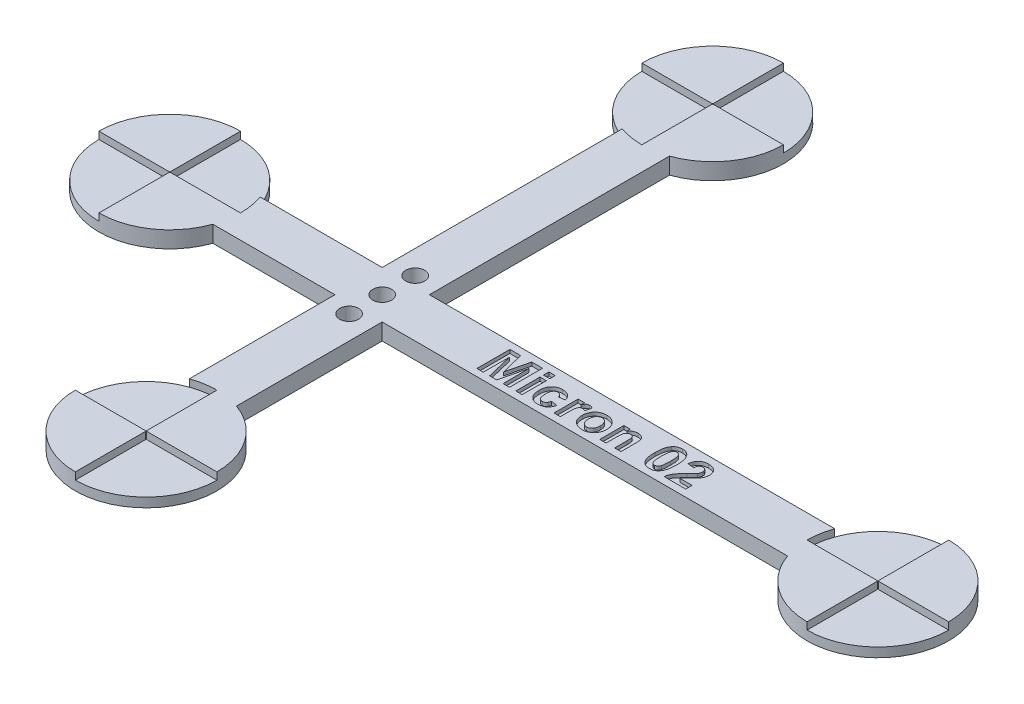
SolidWorks part; units mm, degrees
ref_plane "Front Plane" through (0, 0, 0) normal (0, 0, 1) x (1, 0, 0)
ref_plane "Top Plane" through (0, 0, 0) normal (0, 1, 0) x (1, 0, 0)
ref_plane "Right Plane" through (0, 0, 0) normal (1, 0, 0) x (0, 0, -1)
sketch "Sketch1" plane through (0, 0, 0) normal (0, 1, 0) x (1, 0, 0)
  line L0 (0, 0) -> (150, 0) construction
  line L1 (45, 70) -> (45, -50) construction
  line L2 (40, 55.8579) -> (40, 5)
  line L3 (50, 55.8579) -> (50, 5)
  line L4 (14.1421, 5) -> (40, 5)
  line L5 (14.1421, -5) -> (40, -5)
  line L6 (50, 5) -> (135.8579, 5)
  line L7 (40, -5) -> (40, -35.8579)
  line L8 (50, -5) -> (135.8579, -5)
  line L9 (50, -5) -> (50, -35.8579)
  arc A0 (14.1421, 5) -> (14.1421, -5) centre (0, 0) ccw
  arc A1 (135.8579, -5) -> (135.8579, 5) centre (150, 0) ccw
  arc A2 (50, 55.8579) -> (40, 55.8579) centre (45, 70) ccw
  arc A3 (40, -35.8579) -> (50, -35.8579) centre (45, -50) ccw
  dimension "D1" = 30
  dimension "D3" = 30
  dimension "D5" = 30
  dimension "D6" = 30
  dimension "D2" = 150
  dimension "D4" = 45
  dimension "D7" = 70
  dimension "D8" = 120
  dimension "D9" = 5
  dimension "D10" = 5
  dimension "D11" = 5
  dimension "D12" = 5
extrude "Boss-Extrude1" add sketch "Sketch1" along normal blind 3.5
sketch "Sketch2" plane through (0, 3.5, 0) normal (0, 1, 0) x (1, 0, 0)
  line L0 (45, -65) -> (45, -50.1)
  line L1 (-15, 0) -> (-0.1, 0)
  line L2 (30, 70) -> (44.9, 70)
  line L3 (0, 15) -> (0, 0.1)
  line L4 (150, 15) -> (150, 0.1)
  line L5 (30, -50) -> (44.9, -50)
  line L6 (45.1, 70) -> (60, 70)
  line L7 (45, 70.1) -> (45, 85)
  line L8 (45, 55) -> (45, 69.9)
  line L9 (45, -49.9) -> (45, -35)
  line L10 (45.1, -50) -> (60, -50)
  line L11 (135, 0) -> (149.9, 0)
  line L12 (0.1, 0) -> (15, 0)
  line L13 (0, -0.1) -> (0, -15)
  line L14 (150, -0.1) -> (150, -15)
  line L15 (150.1, 0) -> (165, 0)
  arc A0 (15, 0) -> (0, 15) centre (0, 0) ccw
  arc A1 (150, -15) -> (165, 0) centre (150, 0) ccw
  arc A2 (30, 70) -> (45, 55) centre (45, 70) ccw
  arc A3 (45, -35) -> (30, -50) centre (45, -50) ccw
  arc A4 (0, 0.1) -> (-0.1, 0) centre (0, 0) ccw
  arc A5 (45, 69.9) -> (45.1, 70) centre (45, 70) ccw
  arc A6 (149.9, 0) -> (150, -0.1) centre (150, 0) ccw
  arc A7 (44.9, -50) -> (45, -50.1) centre (45, -50) ccw
  arc A8 (45, 70.1) -> (44.9, 70) centre (45, 70) ccw
  arc A9 (60, 70) -> (45, 85) centre (45, 70) ccw
  arc A10 (45, -65) -> (60, -50) centre (45, -50) ccw
  arc A11 (45.1, -50) -> (45, -49.9) centre (45, -50) ccw
  arc A12 (-15, 0) -> (0, -15) centre (0, 0) ccw
  arc A13 (0, -0.1) -> (0.1, 0) centre (0, 0) ccw
  arc A14 (150.1, 0) -> (150, 0.1) centre (150, 0) ccw
  arc A15 (150, 15) -> (135, 0) centre (150, 0) ccw
  arc A16 (40, -35.8579) -> (50, -35.8579) centre (45, -50) ccw construction
  arc A17 (50, 55.8579) -> (40, 55.8579) centre (45, 70) ccw construction
  dimension "D1" = 0.2
  dimension "D2" = 0.2
  dimension "D3" = 0.2
  dimension "D4" = 0.2
extrude "Cut-Extrude1" cut sketch "Sketch2" against normal blind 1.52
sketch "Sketch3" plane through (0, 3.5, 0) normal (0, 1, 0) x (1, 0, 0)
  line L0 (45, -49.9) -> (45, -35) construction
  line L1 (45, 7) -> (45, -7) construction
  circle A0 centre (45, 0) radius 2
  circle A1 centre (45, 7) radius 2
  circle A2 centre (45, -7) radius 2
  point P2 (45, 0)
  dimension "D2" = 4
  dimension "D3" = 4
  dimension "D4" = 4
  dimension "D1" = 14
extrude "Cut-Extrude2" cut sketch "Sketch3" against normal through all
sketch "Sketch5" plane through (0, 3.5, 0) normal (0, 1, 0) x (1, 0, 0)
  line L0 (67.9289, -3.5) -> (117.9289, -3.5) construction
  line L1 (50, -5) -> (135.8579, -5) construction
  text T0 "Micron 02" font "Arial" height 7
  point P4 (92.9289, -3.5)
  point P5 (92.9289, -5)
  dimension "D1" = 1.5
  dimension "D2" = 50
extrude "Cut-Extrude3" cut sketch "Sketch5" against normal blind 0.75
